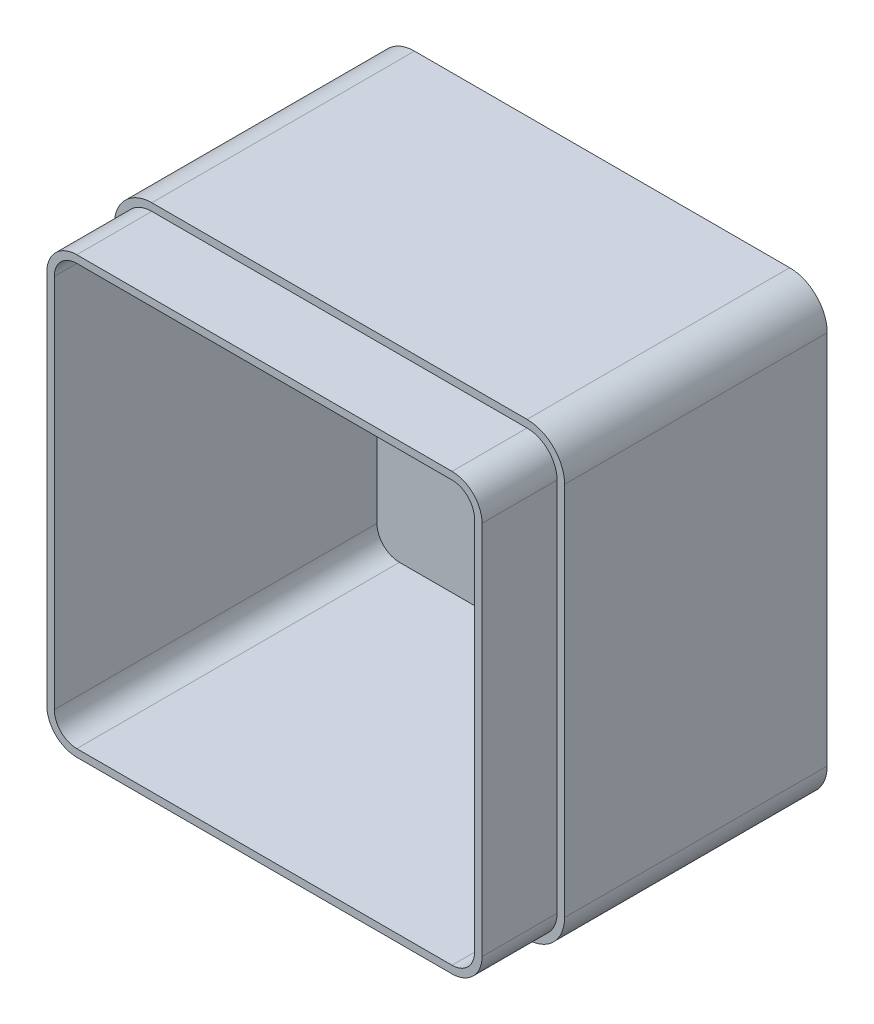
SolidWorks part; units mm, degrees
ref_plane "Front Plane" through (0, 0, 0) normal (0, 0, 1) x (1, 0, 0)
ref_plane "Top Plane" through (0, 0, 0) normal (0, 1, 0) x (1, 0, 0)
ref_plane "Right Plane" through (0, 0, 0) normal (1, 0, 0) x (0, 0, -1)
sketch "Sketch2" plane through (0, 0, 0) normal (0, 0, 1) x (1, 0, 0)
  line L1 (0, 0) -> (120, 0)
  line L2 (0, 0) -> (0, 120)
  line L3 (0, 120) -> (120, 120)
  line L4 (120, 0) -> (120, 120)
  dimension "D1" = 120
  dimension "D2" = 120
extrude "Boss-Extrude1" add sketch "Sketch2" along normal blind 90
fillet "Fillet1" radius 10 4 edges at (0, 0, 45) (0, 120, 45) (120, 120, 45) (120, 0, 45)
shell "Shell1" thickness 4
sketch "Sketch4" plane through (0, 0, 90) normal (0, 0, 1) x (1, 0, 0)
  line L4 (0, 110) -> (0, 10)
  line L5 (10, 0) -> (110, 0)
  line L6 (120, 10) -> (120, 110)
  line L7 (110, 120) -> (10, 120)
  line L8 (0, 110) -> (0, 10)
  line L9 (10, 0) -> (110, 0)
  line L10 (120, 10) -> (120, 110)
  line L11 (110, 120) -> (10, 120)
  line L16 (2, 110) -> (2, 10)
  line L17 (10, 2) -> (110, 2)
  line L18 (118, 10) -> (118, 110)
  line L19 (110, 118) -> (10, 118)
  line L20 (2, 110) -> (2, 10)
  line L21 (10, 2) -> (110, 2)
  line L22 (118, 10) -> (118, 110)
  line L23 (110, 118) -> (10, 118)
  arc A4 (0, 10) -> (10, 0) centre (10, 10) ccw
  arc A5 (110, 0) -> (120, 10) centre (110, 10) ccw
  arc A6 (120, 110) -> (110, 120) centre (110, 110) ccw
  arc A7 (10, 120) -> (0, 110) centre (10, 110) ccw
  arc A8 (0, 10) -> (10, 0) centre (10, 10) ccw
  arc A9 (110, 0) -> (120, 10) centre (110, 10) ccw
  arc A10 (120, 110) -> (110, 120) centre (110, 110) ccw
  arc A11 (10, 120) -> (0, 110) centre (10, 110) ccw
  arc A16 (2, 10) -> (10, 2) centre (10, 10) ccw
  arc A17 (110, 2) -> (118, 10) centre (110, 10) ccw
  arc A18 (118, 110) -> (110, 118) centre (110, 110) ccw
  arc A19 (10, 118) -> (2, 110) centre (10, 110) ccw
  arc A20 (2, 10) -> (10, 2) centre (10, 10) ccw
  arc A21 (110, 2) -> (118, 10) centre (110, 10) ccw
  arc A22 (118, 110) -> (110, 118) centre (110, 110) ccw
  arc A23 (10, 118) -> (2, 110) centre (10, 110) ccw
  dimension "D1" = 0
  dimension "D2" = 2
extrude "Cut-Extrude2" cut sketch "Sketch4" against normal blind 20
